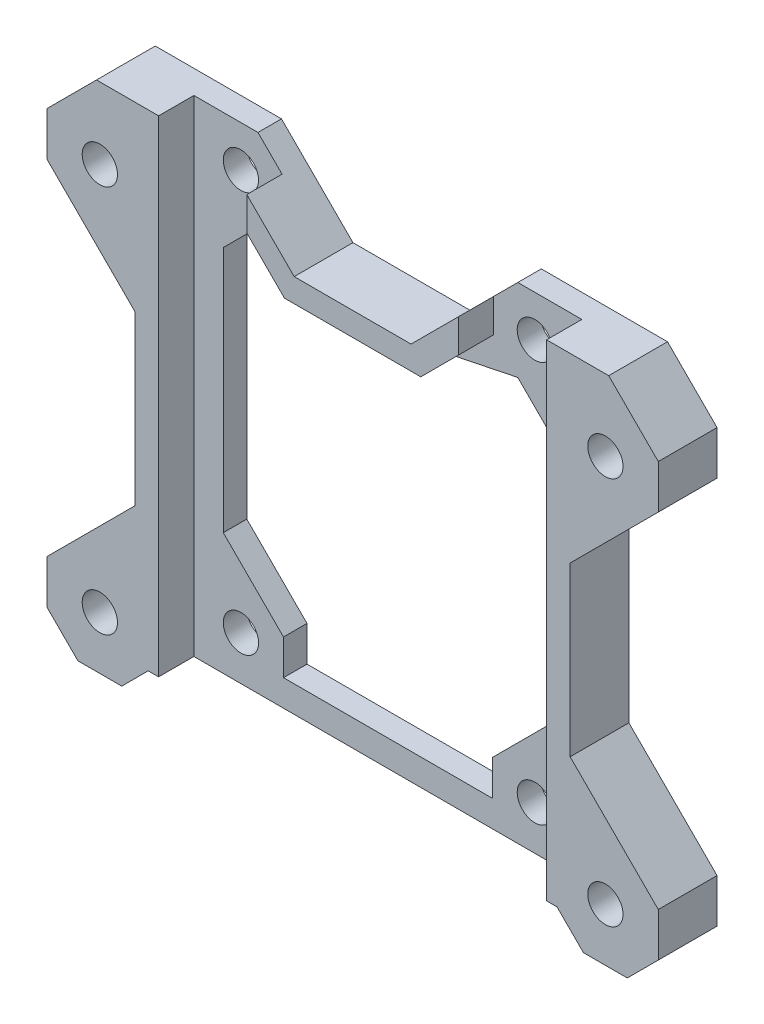
SolidWorks part; units mm, degrees
ref_plane "Front Plane" through (0, 0, 0) normal (0, 0, 1) x (1, 0, 0)
ref_plane "Top Plane" through (0, 0, 0) normal (0, 1, 0) x (1, 0, 0)
ref_plane "Right Plane" through (0, 0, 0) normal (1, 0, 0) x (0, 0, -1)
sketch "Sketch1" plane through (0, 0, 0) normal (0, 0, 1) x (1, 0, 0)
  line L0 (-21.5, 0) -> (21.5, 0) construction
  line L1 (21.5, 0) -> (21.5, 60) construction
  line L2 (21.5, 60) -> (-21.5, 60) construction
  line L3 (-21.5, 60) -> (-21.5, 0) construction
  line L4 (-21.5, 33) -> (21.5, 33) construction
  line L5 (0, 0) -> (0, 60) construction
  line L6 (-14, -2.1213) -> (-11, -2.1213)
  line L7 (-8.8787, 0) -> (-8.8787, 3)
  line L8 (-8.8787, 3) -> (-11, 5.1213)
  line L9 (-11, 5.1213) -> (-14, 5.1213)
  line L10 (-14, 5.1213) -> (-16.1213, 3)
  line L11 (-16.1213, 3) -> (-16.1213, 0)
  line L12 (-16.1213, 0) -> (-14, -2.1213)
  line L13 (-11, -2.1213) -> (-8.8787, 0)
  line L14 (-4.9706, 33) -> (-21.5, 49.5294) construction
  line L16 (-23.364, 37.5) -> (-21.7843, 39.0797)
  line L17 (-21.7843, 39.0797) -> (-13.9497, 39.0797)
  line L18 (-16.5, -2.25) -> (-17.386, -2.25)
  line L19 (-5.799, 31) -> (-11.0503, 32.0797)
  line L23 (-9, 34.1299) -> (-9, 37.0294)
  line L24 (-9, 37.0294) -> (-11.0503, 39.0797)
  line L25 (-11.0503, 39.0797) -> (-13.9497, 39.0797)
  line L26 (-13.9497, 39.0797) -> (-16, 37.0294)
  line L27 (-16, 37.0294) -> (-16, 34.1299)
  line L28 (-16, 34.1299) -> (-13.9497, 32.0797)
  line L29 (-13.9497, 32.0797) -> (-11.0503, 32.0797)
  line L30 (-11.0503, 32.0797) -> (-9, 34.1299)
  line L39 (-14, 0) -> (-14, 42.0294) construction
  line L40 (-16.5, 0) -> (-16.5, 44.5294) construction
  line L49 (-23.364, 37.5) -> (-26, 34.864)
  line L50 (-26, 34.864) -> (-26, 31.136)
  line L51 (-26, 31.136) -> (-23.364, 28.5)
  line L52 (-23.364, 28.5) -> (-19.636, 28.5)
  line L53 (-19.636, 28.5) -> (-17, 31.136)
  line L54 (-17, 31.136) -> (-17, 34.864)
  line L55 (-17, 34.864) -> (-19.636, 37.5)
  line L56 (-19.636, 37.5) -> (-23.364, 37.5)
  line L57 (-23.364, 4.5) -> (-26, 1.864)
  line L58 (-26, 1.864) -> (-26, -1.864)
  line L59 (-26, -1.864) -> (-23.364, -4.5)
  line L60 (-23.364, -4.5) -> (-19.636, -4.5)
  line L61 (-19.636, -4.5) -> (-17, -1.864)
  line L62 (-17, -1.864) -> (-17, 1.864)
  line L63 (-17, 1.864) -> (-19.636, 4.5)
  line L64 (-19.636, 4.5) -> (-23.364, 4.5)
  line L65 (23.364, -4.5) -> (26, -1.864)
  line L66 (26, -1.864) -> (26, 1.864)
  line L67 (26, 1.864) -> (23.364, 4.5)
  line L68 (23.364, 4.5) -> (19.636, 4.5)
  line L69 (19.636, 4.5) -> (17, 1.864)
  line L70 (17, 1.864) -> (17, -1.864)
  line L71 (17, -1.864) -> (19.636, -4.5)
  line L72 (19.636, -4.5) -> (23.364, -4.5)
  line L73 (19.636, 28.5) -> (23.364, 28.5)
  line L74 (23.364, 28.5) -> (26, 31.136)
  line L75 (26, 31.136) -> (26, 34.864)
  line L76 (26, 34.864) -> (23.364, 37.5)
  line L77 (23.364, 37.5) -> (19.636, 37.5)
  line L78 (19.636, 37.5) -> (17, 34.864)
  line L79 (17, 34.864) -> (17, 31.136)
  line L80 (17, 31.136) -> (19.636, 28.5)
  line L89 (-12, 45) -> (-12, 71.0139) construction
  line L90 (12, 45) -> (12, 71.0139) construction
  line L92 (0, 0) -> (-8.8787, 0)
  line L94 (0, -2.25) -> (-16.5, -2.25)
  line L95 (-16.5, -2.25) -> (-16.5, 34.364)
  line L96 (-9, 37.0294) -> (-4.9706, 33)
  line L98 (0, 33) -> (-4.9706, 33)
  line L100 (-5.799, 31) -> (0, 31)
  line L101 (0, -2.25) -> (-16.5, -2.25) construction
  line L109 (-23.364, 4.5) -> (-18.5, 9.364)
  line L110 (-18.5, 9.364) -> (-18.5, 23.636)
  line L111 (-18.5, 23.636) -> (-23.364, 28.5)
  line L112 (-11.0503, 32.0797) -> (-14, 29.1299)
  line L113 (-14, 29.1299) -> (-14, 8.1213)
  line L114 (-14, 8.1213) -> (-11, 5.1213)
  line L119 (-17, 34.864) -> (-16.5, 34.364)
  line L125 (-9, 34.201) -> (-5.799, 31)
  line L126 (-9, 34.1299) -> (-8.9645, 34.1655)
  circle A1 centre (-21.5, 33) radius 1.5
  circle A2 centre (-21.5, 0) radius 1.5
  circle A3 centre (21.5, 0) radius 1.5
  circle A4 centre (21.5, 33) radius 1.5
  circle A6 centre (-12.5, 1.5) radius 1.5
  circle A8 centre (-12.5, 35.5797) radius 1.5
  circle A10 centre (0, 45) radius 12 construction
  circle A11 centre (-12.5, 1.5) radius 3.6213 construction
  circle A13 centre (-12.5, 35.5797) radius 3.5 construction
  circle A16 centre (-21.5, 33) radius 4.5 construction
  circle A17 centre (-21.5, 0) radius 4.5 construction
  circle A18 centre (21.5, 0) radius 4.5 construction
  circle A19 centre (21.5, 33) radius 4.5 construction
  dimension "D4" = 2.25
  dimension "D5" = 24
  dimension "D7" = 45
  dimension "D8" = 7
  dimension "D9" = 3
  dimension "D10" = 9
  dimension "D11" = 9
  dimension "D12" = 3
  dimension "D13" = 9
  dimension "D14" = 9
  dimension "D1" = 43
  dimension "D2" = 33
  dimension "D3" = 27
  dimension "D6" = 12.5
  dimension "D15" = 2.5
  dimension "D16" = 2
  dimension "D17" = 2
  dimension "D18" = 45
  dimension "D19" = 45
  dimension "D24" = 2
sketch "Sketch11" plane through (0, 0, 0) normal (0, 0, 1) x (1, 0, 0)
  line L0 (0, -2.25) -> (-16.5, -2.25) construction
  line L1 (-5.799, 31) -> (-11.0503, 32.0797) construction
  line L2 (-19.636, -4.5) -> (-17, -1.864) construction
  line L3 (-23.364, -4.5) -> (-19.636, -4.5) construction
  line L4 (-26, -1.864) -> (-23.364, -4.5) construction
  line L5 (-26, 1.864) -> (-26, -1.864) construction
  line L6 (-23.364, 4.5) -> (-26, 1.864) construction
  line L7 (-23.364, 4.5) -> (-18.5, 9.364) construction
  line L8 (-18.5, 9.364) -> (-18.5, 23.636) construction
  line L9 (0, 0) -> (-8.8787, 0) construction
  line L10 (-8.8787, 0) -> (-8.8787, 3) construction
  line L11 (-8.8787, 3) -> (-11, 5.1213) construction
  line L12 (-14, 8.1213) -> (-11, 5.1213) construction
  line L13 (-14, 29.1299) -> (-14, 8.1213) construction
  line L14 (0, 0) -> (0, 60) construction
  line L15 (-18.5, 23.636) -> (-23.364, 28.5) construction
  line L16 (-26, 31.136) -> (-23.364, 28.5) construction
  line L17 (-26, 34.864) -> (-26, 31.136) construction
  line L18 (-23.364, 37.5) -> (-26, 34.864) construction
  line L19 (-23.364, 37.5) -> (-21.7843, 39.0797) construction
  line L20 (-21.7843, 39.0797) -> (-13.9497, 39.0797) construction
  line L21 (-11.0503, 39.0797) -> (-13.9497, 39.0797) construction
  line L22 (-9, 37.0294) -> (-11.0503, 39.0797) construction
  line L23 (-9, 37.0294) -> (-4.9706, 33) construction
  line L24 (0, 33) -> (-4.9706, 33) construction
  line L25 (-5.799, 31) -> (0, 31) construction
  line L29 (-11.0503, 32.0797) -> (-14, 29.1299) construction
  line L30 (16.5, -2.25) -> (-16.5, -2.25)
  line L31 (-16.5, -2.25) -> (-17.386, -2.25) construction
  line L32 (-19.636, -4.5) -> (-17.386, -2.25)
  line L33 (-23.364, -4.5) -> (-19.636, -4.5)
  line L34 (-26, -1.864) -> (-23.364, -4.5)
  line L35 (-26, 1.864) -> (-26, -1.864)
  line L36 (-23.364, 4.5) -> (-26, 1.864)
  line L37 (-23.364, 4.5) -> (-18.5, 9.364)
  line L38 (-18.5, 9.364) -> (-18.5, 23.636)
  line L39 (8.8787, 0) -> (-8.8787, 0)
  line L40 (-8.8787, 0) -> (-8.8787, 3)
  line L41 (-8.8787, 3) -> (-11, 5.1213)
  line L42 (-14, 8.1213) -> (-11, 5.1213)
  line L43 (-14, 29.1299) -> (-14, 8.1213)
  line L44 (0, 0) -> (0, 60) construction
  line L45 (-18.5, 23.636) -> (-23.364, 28.5)
  line L46 (-26, 31.136) -> (-23.364, 28.5)
  line L47 (-26, 34.864) -> (-26, 31.136)
  line L48 (-23.364, 37.5) -> (-26, 34.864)
  line L49 (-23.364, 37.5) -> (-21.7843, 39.0797)
  line L50 (-21.7843, 39.0797) -> (-13.9497, 39.0797)
  line L51 (-11.0503, 39.0797) -> (-13.9497, 39.0797)
  line L52 (-9, 37.0294) -> (-11.0503, 39.0797)
  line L53 (-9, 37.0294) -> (-4.9706, 33)
  line L54 (4.9706, 33) -> (-4.9706, 33)
  line L55 (-5.799, 31) -> (5.799, 31)
  line L56 (5.799, 31) -> (11.0503, 32.0797)
  line L59 (-11.0503, 32.0797) -> (-14, 29.1299)
  line L60 (11.0503, 32.0797) -> (14, 29.1299)
  line L64 (9, 37.0294) -> (4.9706, 33)
  line L65 (9, 37.0294) -> (11.0503, 39.0797)
  line L66 (11.0503, 39.0797) -> (13.9497, 39.0797)
  line L67 (21.7843, 39.0797) -> (13.9497, 39.0797)
  line L68 (23.364, 37.5) -> (21.7843, 39.0797)
  line L69 (23.364, 37.5) -> (26, 34.864)
  line L70 (26, 34.864) -> (26, 31.136)
  line L71 (26, 31.136) -> (23.364, 28.5)
  line L72 (18.5, 23.636) -> (23.364, 28.5)
  line L73 (14, 29.1299) -> (14, 8.1213)
  line L74 (14, 8.1213) -> (11, 5.1213)
  line L75 (8.8787, 3) -> (11, 5.1213)
  line L76 (8.8787, 0) -> (8.8787, 3)
  line L77 (18.5, 9.364) -> (18.5, 23.636)
  line L78 (23.364, 4.5) -> (18.5, 9.364)
  line L79 (23.364, 4.5) -> (26, 1.864)
  line L80 (26, 1.864) -> (26, -1.864)
  line L81 (26, -1.864) -> (23.364, -4.5)
  line L82 (23.364, -4.5) -> (19.636, -4.5)
  line L83 (19.636, -4.5) -> (17.386, -2.25)
  line L84 (16.5, -2.25) -> (17.386, -2.25)
  line L85 (-16.5, -2.25) -> (-17.386, -2.25)
  line L86 (-5.799, 31) -> (-11.0503, 32.0797)
  circle A0 centre (-12.5, 1.5) radius 1.5 construction
  circle A1 centre (-12.5, 35.5797) radius 1.5 construction
  circle A2 centre (-12.5, 1.5) radius 1.5
  circle A3 centre (-12.5, 35.5797) radius 1.5
  circle A4 centre (12.5, 35.5797) radius 1.5
  circle A5 centre (12.5, 1.5) radius 1.5
extrude "Boss-Extrude4" add sketch "Sketch11" along normal blind 2
sketch "Sketch12" plane through (0, 0, 2) normal (0, 0, 1) x (1, 0, 0)
  line L1 (-19.636, -4.5) -> (-17, -1.864) construction
  line L2 (-23.364, -4.5) -> (-19.636, -4.5) construction
  line L3 (-26, -1.864) -> (-23.364, -4.5) construction
  line L4 (-26, 1.864) -> (-26, -1.864) construction
  line L5 (-23.364, 4.5) -> (-26, 1.864) construction
  line L6 (-23.364, 4.5) -> (-18.5, 9.364) construction
  line L7 (-18.5, 9.364) -> (-18.5, 23.636) construction
  line L8 (-16.5, -2.25) -> (-16.5, 34.364) construction
  line L9 (-18.5, 23.636) -> (-23.364, 28.5) construction
  line L10 (-26, 31.136) -> (-23.364, 28.5) construction
  line L11 (-26, 34.864) -> (-26, 31.136) construction
  line L12 (-23.364, 37.5) -> (-26, 34.864) construction
  line L13 (-23.364, 37.5) -> (-21.7843, 39.0797) construction
  line L14 (-21.7843, 39.0797) -> (-13.9497, 39.0797) construction
  line L15 (-16.5, 0) -> (-16.5, 44.5294) construction
  line L16 (-9, 34.1299) -> (-9, 37.0294) construction
  line L17 (-9, 37.0294) -> (-4.9706, 33) construction
  line L18 (0, 33) -> (-4.9706, 33) construction
  line L19 (-5.799, 31) -> (0, 31) construction
  line L20 (-9, 34.201) -> (-5.799, 31) construction
  line L21 (0, 0) -> (0, 60) construction
  line L22 (-16.5, -2.25) -> (-17.386, -2.25) construction
  line L23 (-19.636, -4.5) -> (-17.386, -2.25)
  line L24 (-23.364, -4.5) -> (-19.636, -4.5)
  line L25 (-26, -1.864) -> (-23.364, -4.5)
  line L26 (-26, 1.864) -> (-26, -1.864)
  line L27 (-23.364, 4.5) -> (-26, 1.864)
  line L28 (-23.364, 4.5) -> (-18.5, 9.364)
  line L29 (-18.5, 9.364) -> (-18.5, 23.636)
  line L30 (-16.5, -2.25) -> (-16.5, 34.364)
  line L31 (-18.5, 23.636) -> (-23.364, 28.5)
  line L32 (-26, 31.136) -> (-23.364, 28.5)
  line L33 (-26, 34.864) -> (-26, 31.136)
  line L34 (-23.364, 37.5) -> (-26, 34.864)
  line L35 (-23.364, 37.5) -> (-21.7843, 39.0797)
  line L36 (-21.7843, 39.0797) -> (-16.5, 39.0797)
  line L37 (-16.5, 0) -> (-16.5, 39.0797)
  line L38 (-9, 34.201) -> (-9, 37.0294)
  line L39 (-9, 37.0294) -> (-4.9706, 33)
  line L40 (4.9706, 33) -> (-4.9706, 33)
  line L41 (-5.799, 31) -> (5.799, 31)
  line L42 (-9, 34.201) -> (-5.799, 31)
  line L43 (0, 0) -> (0, 60) construction
  line L44 (9, 34.201) -> (5.799, 31)
  line L45 (9, 37.0294) -> (4.9706, 33)
  line L46 (9, 34.201) -> (9, 37.0294)
  line L47 (16.5, 0) -> (16.5, 39.0797)
  line L48 (21.7843, 39.0797) -> (16.5, 39.0797)
  line L49 (23.364, 37.5) -> (21.7843, 39.0797)
  line L50 (23.364, 37.5) -> (26, 34.864)
  line L51 (26, 34.864) -> (26, 31.136)
  line L52 (26, 31.136) -> (23.364, 28.5)
  line L53 (18.5, 23.636) -> (23.364, 28.5)
  line L54 (16.5, -2.25) -> (16.5, 34.364)
  line L55 (18.5, 9.364) -> (18.5, 23.636)
  line L56 (23.364, 4.5) -> (18.5, 9.364)
  line L57 (23.364, 4.5) -> (26, 1.864)
  line L58 (26, 1.864) -> (26, -1.864)
  line L59 (26, -1.864) -> (23.364, -4.5)
  line L60 (23.364, -4.5) -> (19.636, -4.5)
  line L61 (19.636, -4.5) -> (17.386, -2.25)
  line L62 (16.5, -2.25) -> (17.386, -2.25)
  line L63 (-16.5, -2.25) -> (-17.386, -2.25)
  circle A0 centre (-21.5, 0) radius 1.5 construction
  circle A1 centre (-21.5, 0) radius 1.5
  circle A2 centre (-21.5, 33) radius 1.5 construction
  circle A3 centre (-21.5, 33) radius 1.5
  circle A4 centre (21.5, 33) radius 1.5
  circle A5 centre (21.5, 0) radius 1.5
extrude "Boss-Extrude5" add sketch "Sketch12" along normal blind 3
